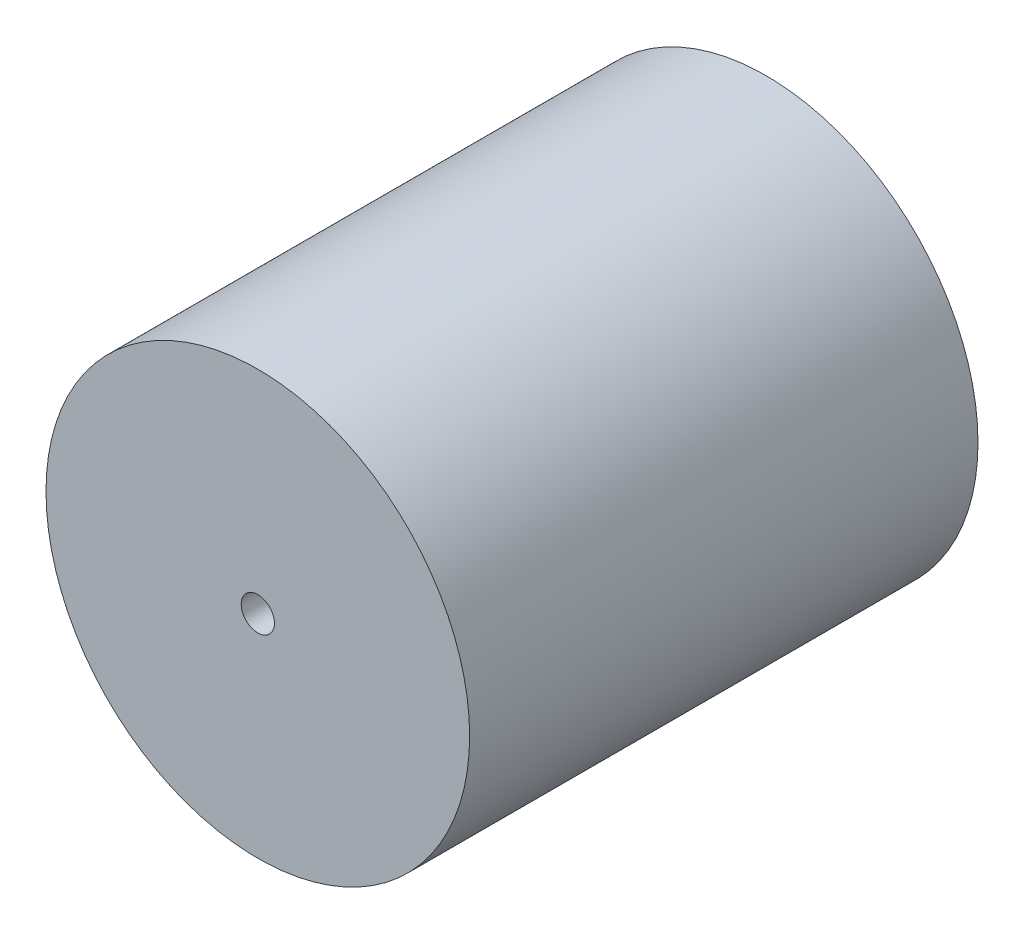
SolidWorks part; units mm, degrees
ref_plane "Front Plane" through (0, 0, 0) normal (0, 0, 1) x (1, 0, 0)
ref_plane "Top Plane" through (0, 0, 0) normal (0, 1, 0) x (1, 0, 0)
ref_plane "Right Plane" through (0, 0, 0) normal (1, 0, 0) x (0, 0, -1)
sketch "Sketch1" plane through (0, 0, 0) normal (0, 0, 1) x (1, 0, 0)
  line L0 (50.8, 0) -> (50.8, -25.4)
  line L1 (0, 0) -> (50.8, 0)
  line L5 (50.8, -25.4) -> (0, -25.4)
  line L6 (0, -25.4) -> (0, 0)
  circle A0 centre (28.575, 38.1) radius 31.75
  circle A1 centre (28.575, 38.1) radius 2.4892
  dimension "D5" = 3.175
  dimension "D3" = 63.5
  dimension "D6" = 4.9784
  dimension "D1" = 50.8
  dimension "D2" = 38.1
  dimension "D4" = 25.4
extrude "Boss-Extrude1" add sketch "Sketch1" along normal mid plane 76.2 contours L0 A0 L1
